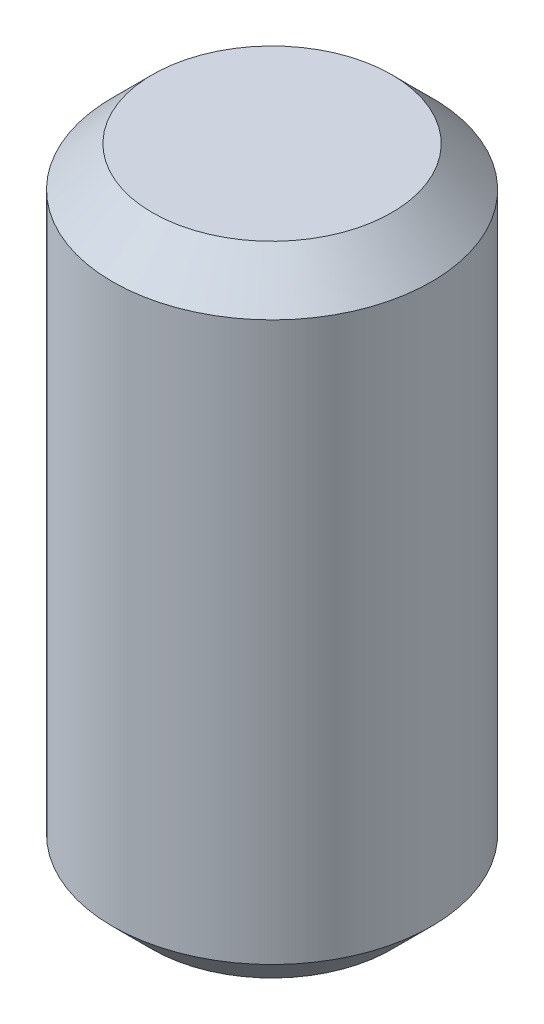
SolidWorks part; units mm, degrees
ref_plane "Front Plane" through (0, 0, 0) normal (0, 0, 1) x (1, 0, 0)
ref_plane "Top Plane" through (0, 0, 0) normal (0, 1, 0) x (1, 0, 0)
ref_plane "Right Plane" through (0, 0, 0) normal (1, 0, 0) x (0, 0, -1)
sketch "Sketch1" plane through (0, 0, 0) normal (0, 1, 0) x (1, 0, 0)
  circle A0 centre (0, 0) radius 2
  dimension "D1" = 4
extrude "Boss-Extrude1" add sketch "Sketch1" along normal blind 8
chamfer "Chamfer1" distance 0.5 angle 45 2 edges at (0, 8, 2) (0, 0, 2)
